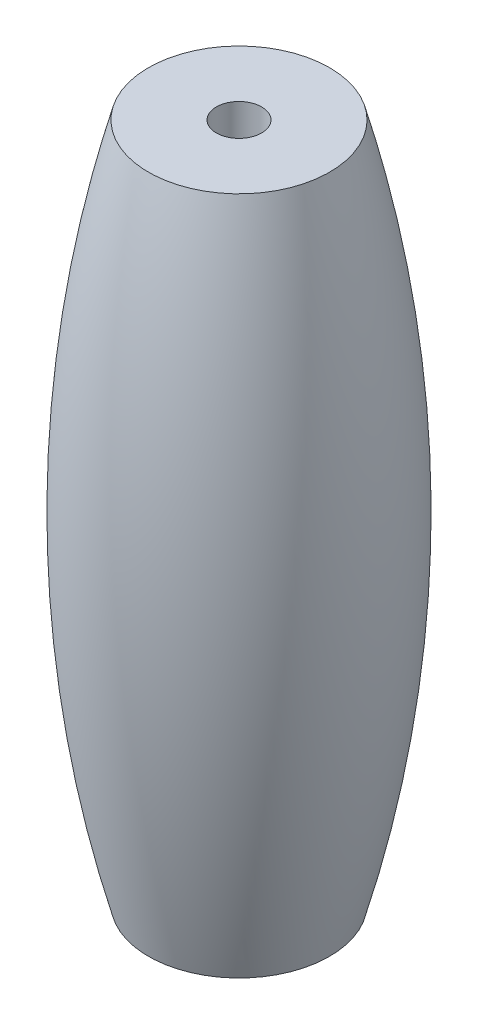
SolidWorks part; units mm, degrees
ref_plane "Plan de face" through (0, 0, 0) normal (0, 0, 1) x (1, 0, 0)
ref_plane "Plan de dessus" through (0, 0, 0) normal (0, 1, 0) x (1, 0, 0)
ref_plane "Plan de droite" through (0, 0, 0) normal (1, 0, 0) x (0, 0, -1)
sketch "Esquisse1" plane through (0, 0, 0) normal (0, 0, 1) x (1, 0, 0)
  line L0 (0, 0) -> (0, 30) construction
  line L1 (0, 15) -> (6, 15) construction
  line L2 (0, 0) -> (4, 0)
  line L3 (0, 30) -> (4, 30)
  line L4 (0, 0) -> (0, 30)
  arc A0 (6, 15) -> (4, 0) centre (-51.25, 15) cw
  arc A1 (6, 15) -> (4, 30) centre (-51.25, 15) ccw
  dimension "D1" = 4
  dimension "D3" = 6
  dimension "D4" = 30
revolve "Révolution1" add sketch "Esquisse1" angle 360 about L4
sketch "Esquisse2" plane through (0, 30, 0) normal (0, 1, 0) x (1, 0, 0)
  circle A0 centre (0, 0) radius 1
  dimension "D1" = 2
extrude "Enlèv. mat.-Extru.1" cut sketch "Esquisse2" against normal through all
